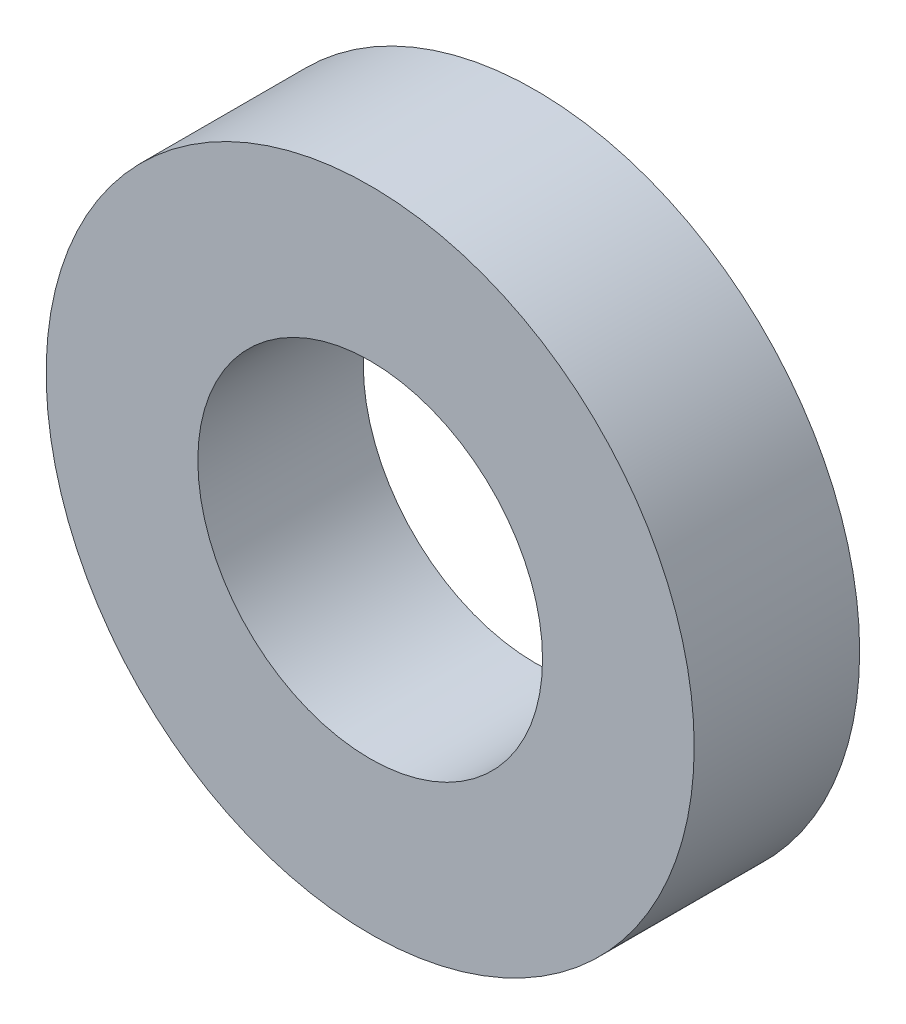
SolidWorks part; units mm, degrees
ref_plane "Front Plane" through (0, 0, 0) normal (0, 0, 1) x (1, 0, 0)
ref_plane "Top Plane" through (0, 0, 0) normal (0, 1, 0) x (1, 0, 0)
ref_plane "Right Plane" through (0, 0, 0) normal (1, 0, 0) x (0, 0, -1)
sketch "Sketch2" plane through (0, 0, 0) normal (0, 0, 1) x (1, 0, 0)
  circle A0 centre (0, 0) radius 23.5
  point P2 (0, 0)
  dimension "D1" = 47
extrude "Boss-Extrude1" add sketch "Sketch2" along normal blind 12
sketch "Sketch3" plane through (0, 0, 12) normal (0, 0, 1) x (1, 0, 0)
  circle A3 centre (0, 0) radius 12.5
  dimension "D1" = 25
extrude "Cut-Extrude1" cut sketch "Sketch3" against normal through all
